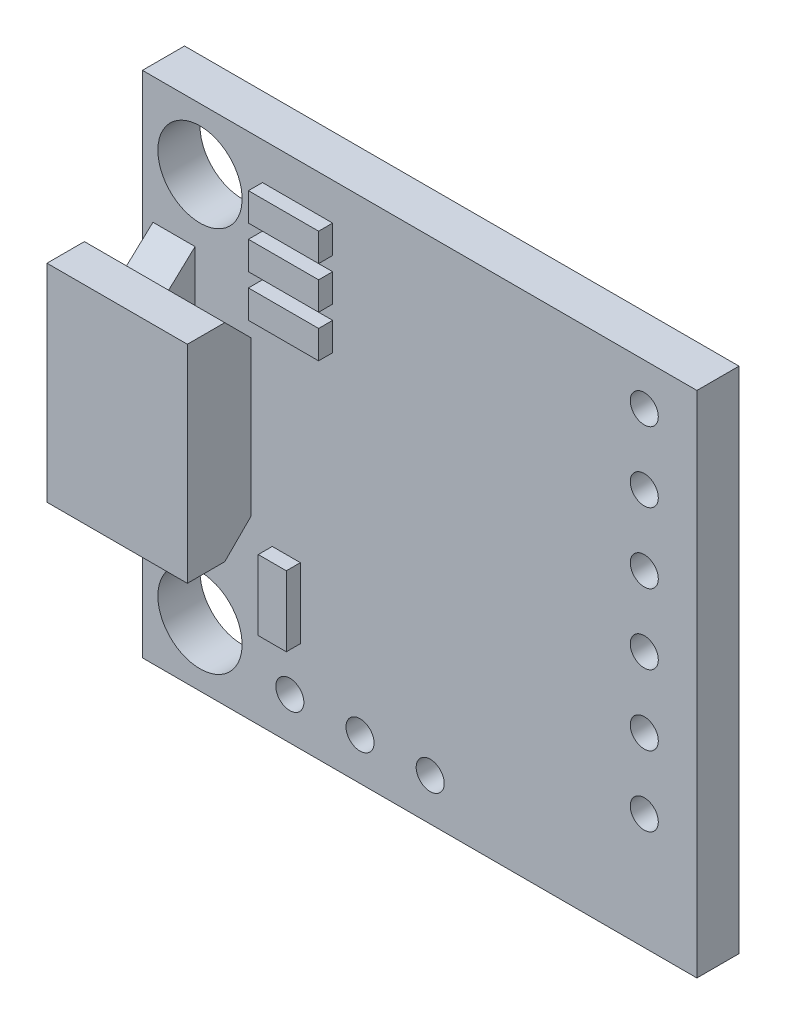
SolidWorks part; units mm, degrees
ref_plane "Front Plane" through (0, 0, 0) normal (0, 0, 1) x (1, 0, 0)
ref_plane "Top Plane" through (0, 0, 0) normal (0, 1, 0) x (1, 0, 0)
ref_plane "Right Plane" through (0, 0, 0) normal (1, 0, 0) x (0, 0, -1)
sketch "Sketch1" plane through (0, 0, 0) normal (0, 0, 1) x (1, 0, 0)
  line L0 (0, 9.2075) -> (0, 0) construction
  line L1 (-10.033, 9.2075) -> (10.033, 9.2075)
  line L2 (-10.033, 9.2075) -> (-10.033, -9.2075)
  line L3 (-10.033, -9.2075) -> (10.033, -9.2075)
  line L4 (10.033, 9.2075) -> (10.033, -9.2075)
  line L5 (0, 0) -> (10.033, 0) construction
  line L6 (-7.9502, 6.985) -> (-7.9502, -6.985) construction
  line L7 (0, 0) -> (-7.9502, 0) construction
  line L14 (-9.4742, 6.985) -> (-10.033, 6.985) construction
  circle A0 centre (-7.9502, 6.985) radius 1.524
  circle A1 centre (-7.9502, -6.985) radius 1.524
  dimension "D3" = 13.97
  dimension "D6" = 3.048
  dimension "D1" = 20.066
  dimension "D2" = 18.415
  dimension "D5" = 0.5588
extrude "Extrude1" add sketch "Sketch1" along normal blind 1.524
sketch "Sketch2" plane through (-10.033, 0, 0) normal (-1, 0, 0) x (0, 0, 1)
  line L0 (3.8354, 3.7465) -> (3.8354, -3.7465)
  line L1 (3.8354, -3.7465) -> (2.4814, -3.7465)
  line L2 (2.4814, -3.7465) -> (1.524, -2.7891)
  line L3 (1.524, 9.2075) -> (1.524, -9.2075) construction
  line L4 (1.524, -2.7891) -> (1.524, 2.7891)
  line L5 (1.524, 2.7891) -> (2.4814, 3.7465)
  line L6 (2.4814, 3.7465) -> (3.8354, 3.7465)
  line L7 (1.524, 0) -> (0, 0) construction
  dimension "D1" = 7.493
  dimension "D2" = 2.3114
extrude "Extrude2" add sketch "Sketch2" along normal blind 1.143 and the other way blind 3.937
sketch "Sketch3" plane through (0, 0, 1.524) normal (0, 0, 1) x (1, 0, 0)
  line L0 (10.033, 9.2075) -> (-10.033, 9.2075) construction
  line L1 (10.033, -9.2075) -> (10.033, 9.2075) construction
  circle A0 centre (8.128, 7.6835) radius 0.508
  dimension "D1" = 1.016
  dimension "D2" = 1.524
  dimension "D3" = 1.905
extrude "Extrude3" cut sketch "Sketch3" against normal through all
pattern_linear "LPattern1" count 6 spacing 2.54 along (0, -1, 0) of "Extrude3"
sketch "Sketch4" plane through (0, 0, 1.524) normal (0, 0, 1) x (1, 0, 0)
  line L0 (-10.033, -2.7891) -> (-10.033, -9.2075) construction
  line L1 (-10.033, -9.2075) -> (10.033, -9.2075) construction
  circle A0 centre (-4.699, -7.6835) radius 0.508
  dimension "D1" = 1.016
  dimension "D2" = 5.334
  dimension "D3" = 1.524
extrude "Extrude4" cut sketch "Sketch4" against normal through all
pattern_linear "LPattern2" count 3 spacing 2.54 along (1, 0, 0) of "Extrude4"
sketch "Sketch5" plane through (0, 0, 1.524) normal (0, 0, 1) x (1, 0, 0)
  line L0 (-10.033, 9.2075) -> (-10.033, 2.7891) construction
  line L1 (-5.6896, 7.8613) -> (-3.1496, 7.8613)
  line L2 (-5.6896, 7.8613) -> (-5.6896, 6.8453)
  line L3 (-5.6896, 6.8453) -> (-3.1496, 6.8453)
  line L4 (-3.1496, 7.8613) -> (-3.1496, 6.8453)
  line L5 (-5.6896, 6.3373) -> (-3.1496, 6.3373)
  line L6 (-5.6896, 6.3373) -> (-5.6896, 5.3213)
  line L7 (-5.6896, 5.3213) -> (-3.1496, 5.3213)
  line L8 (-3.1496, 6.3373) -> (-3.1496, 5.3213)
  line L9 (-5.6896, 4.8133) -> (-3.1496, 4.8133)
  line L10 (-5.6896, 4.8133) -> (-5.6896, 3.7973)
  line L11 (-5.6896, 3.7973) -> (-3.1496, 3.7973)
  line L12 (-3.1496, 4.8133) -> (-3.1496, 3.7973)
  line L13 (-5.334, -3.3655) -> (-4.318, -3.3655)
  line L14 (-5.334, -3.3655) -> (-5.334, -5.9055)
  line L15 (-5.334, -5.9055) -> (-4.318, -5.9055)
  line L16 (-4.318, -3.3655) -> (-4.318, -5.9055)
  line L17 (-5.6896, 6.8453) -> (-5.6896, 6.3373) construction
  line L18 (-5.6896, 5.3213) -> (-5.6896, 4.8133) construction
  line L19 (10.033, 9.2075) -> (-10.033, 9.2075) construction
  line L20 (-10.033, -2.7891) -> (-10.033, -9.2075) construction
  line L21 (-10.033, -9.2075) -> (10.033, -9.2075) construction
  dimension "D1" = 4.3434
  dimension "D2" = 1.3462
  dimension "D3" = 1.524
  dimension "D4" = 1.016
  dimension "D5" = 2.54
  dimension "D6" = 4.699
  dimension "D7" = 1.016
  dimension "D8" = 2.54
  dimension "D9" = 3.302
extrude "KeepAway" add sketch "Sketch5" along normal blind 0.508
sketch "Sketch6" plane through (-11.176, 0, 0) normal (-1, 0, 0) x (0, 0, 1)
  line L0 (1.524, 4.6355) -> (1.524, 2.7891)
  line L1 (1.524, 2.7891) -> (2.4814, 3.7465)
  line L2 (2.4814, 3.7465) -> (1.524, 4.6355)
  line L3 (1.524, -2.7891) -> (1.524, -4.6355)
  line L4 (1.524, -4.6355) -> (2.4814, -3.7465)
  line L5 (2.4814, -3.7465) -> (1.524, -2.7891)
  dimension "D1" = 9.271
extrude "Extrude6" add sketch "Sketch6" against normal blind 1.524 from offset 1.524
